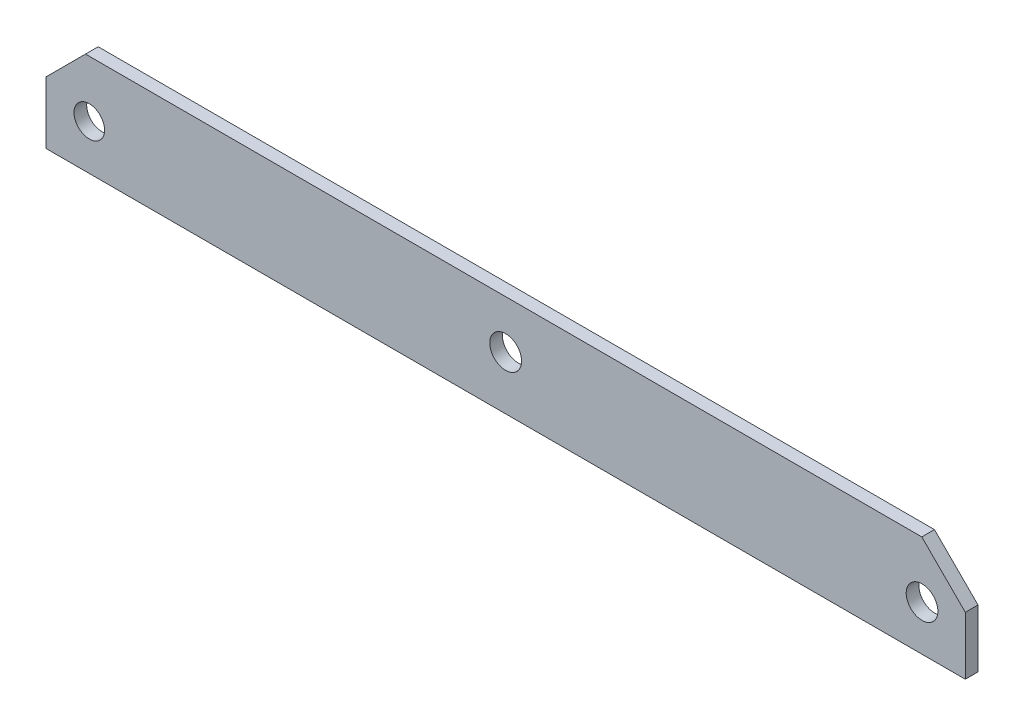
SolidWorks part; units mm, degrees
ref_plane "Front" through (0, 0, 0) normal (0, 0, 1) x (1, 0, 0)
ref_plane "Top" through (0, 0, 0) normal (0, 1, 0) x (1, 0, 0)
ref_plane "Right" through (0, 0, 0) normal (1, 0, 0) x (0, 0, -1)
sketch "Sketch2" plane through (0, 0, 0) normal (0, 0, 1) x (1, 0, 0)
  line L0 (0, 15.5215) -> (9.8785, 25.4)
  line L1 (0, 0) -> (230, 0)
  line L2 (0, 0) -> (0, 25.4)
  line L3 (0, 25.4) -> (230, 25.4)
  line L4 (230, 0) -> (230, 25.4)
  line L5 (219.11, 25.4) -> (230, 14.51)
  circle A0 centre (1.8963, 23.827) radius 1.0969
  circle A1 centre (10.8273, 11.2956) radius 3.825
  circle A2 centre (115, 13.4) radius 3.9795
  circle A3 centre (219.1727, 11.2956) radius 3.9601
  dimension "D1" = 230
  dimension "D2" = 25.4
  dimension "D3" = 12
  dimension "D4" = 115
extrude "Boss-Extrude1" add sketch "Sketch2" along normal blind 3.175 contours L5 L3 L0 L2 L1 L4 A3 A2 A1
